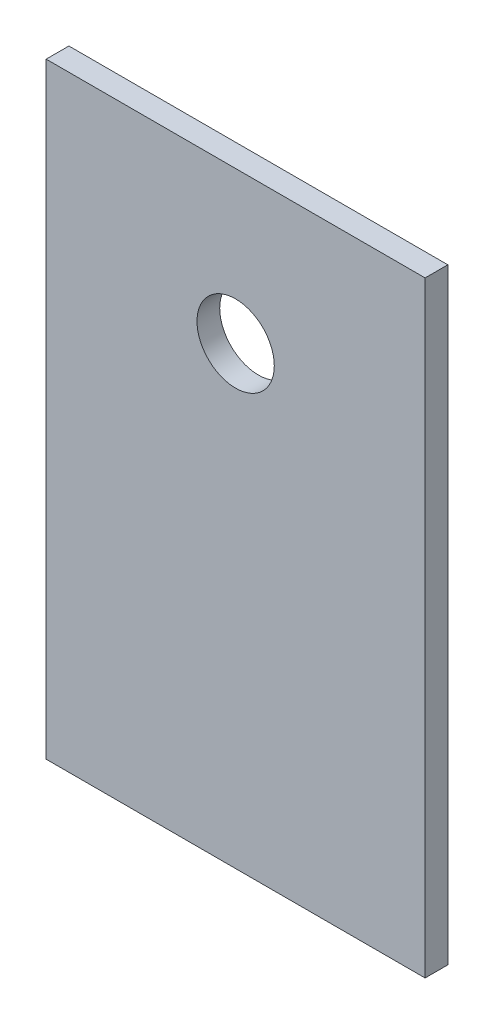
SolidWorks part; units mm, degrees
ref_plane "Płaszczyzna przednia" through (0, 0, 0) normal (0, 0, 1) x (1, 0, 0)
ref_plane "Płaszczyzna górna" through (0, 0, 0) normal (0, 1, 0) x (1, 0, 0)
ref_plane "Płaszczyzna prawa" through (0, 0, 0) normal (1, 0, 0) x (0, 0, -1)
sketch "Szkic1" plane through (0, 0, 0) normal (0, 0, 1) x (1, 0, 0)
  line L1 (-25, -40) -> (25, -40)
  line L2 (-25, -40) -> (-25, 40)
  line L3 (-25, 40) -> (25, 40)
  line L4 (25, -40) -> (25, 40)
  line L5 (-25, -40) -> (25, 40) construction
  line L6 (-25, 40) -> (25, -40) construction
  point P0 (0, 0)
  dimension "D1" = 50
  dimension "D2" = 80
extrude "Dodanie-wyciągnięcie1" add sketch "Szkic1" along normal blind 3 contours L3 L4 L1 L2
hole_wizard "Otwór gwintowany M121" positions "Szkic2" profile "Szkic3" tap size "M12" standard "ISO"
sketch "Szkic2" plane through (0, 0, 3) normal (0, 0, 1) x (1, 0, 0)
  point P0 (0, 20)
  dimension "D1" = 20
sketch "Szkic3" plane through (0, 20, 3) normal (1, 0, 0) x (0, -1, 0)
  line L0 (0, 0) -> (0, 35.8144)
  line L1 (0, 35.8144) -> (5.1, 32.75)
  line L2 (5.1, 32.75) -> (5.1, 0)
  line L5 (5.1, 0) -> (0, 0)
  line L10 (0, 35.8144) -> (-5.1, 32.75) construction
  line L11 (0, -6.35) -> (0, 107.95) construction
  dimension "Średnica wiertła gwintu" = 10.2
  dimension "Głębokość otworu gwintowanego" = 32.75
  dimension "Kąt wiertła" = 118
